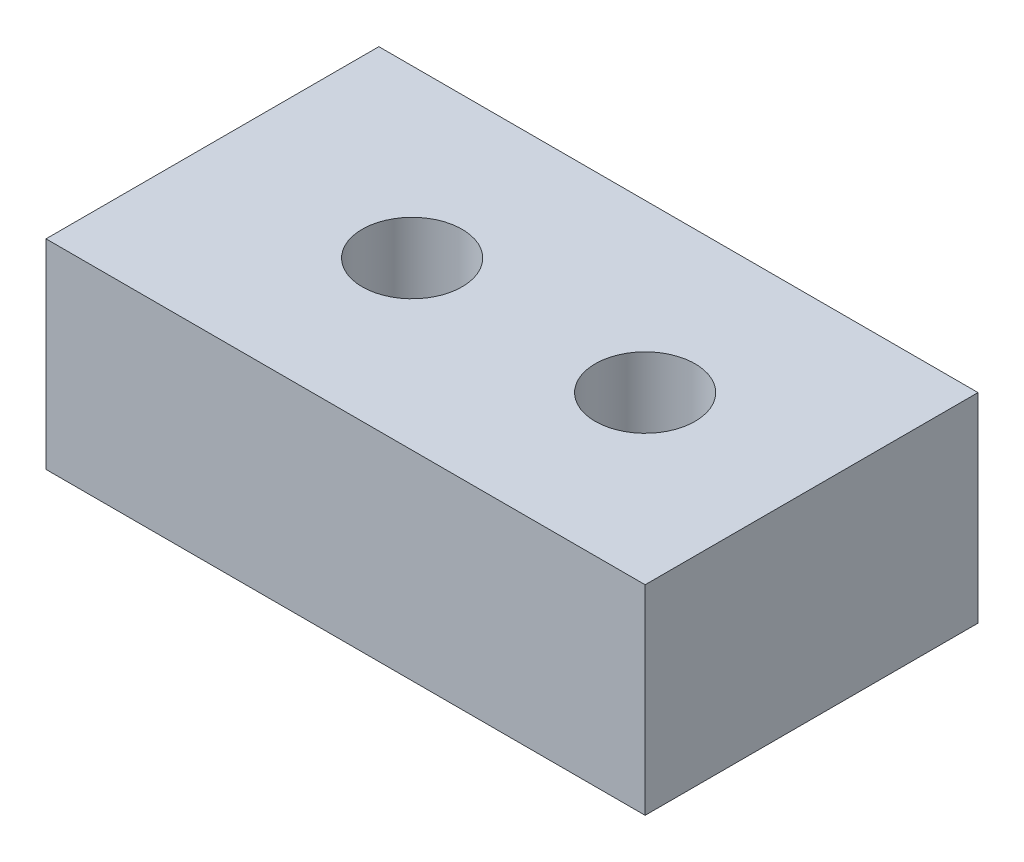
SolidWorks part; units mm, degrees
material "Balsa"
ref_plane "Front Plane" through (0, 0, 0) normal (0, 0, 1) x (1, 0, 0)
ref_plane "Top Plane" through (0, 0, 0) normal (0, 1, 0) x (1, 0, 0)
ref_plane "Right Plane" through (0, 0, 0) normal (1, 0, 0) x (0, 0, -1)
sketch "Sketch1" plane through (0, 0, 0) normal (0, 1, 0) x (1, 0, 0)
  line L1 (-9, -5) -> (9, -5)
  line L2 (-9, -5) -> (-9, 5)
  line L3 (-9, 5) -> (9, 5)
  line L4 (9, -5) -> (9, 5)
  line L5 (-9, -5) -> (9, 5) construction
  line L6 (-9, 5) -> (9, -5) construction
  point P0 (0, 0)
  dimension "D1" = 10
  dimension "D2" = 18
extrude "Boss-Extrude1" add sketch "Sketch1" along normal blind 6
sketch "Sketch2" plane through (0, 6, 0) normal (0, 1, 0) x (1, 0, 0)
  line L0 (-9, 0) -> (9, 0) construction
  line L1 (-9, 5) -> (-9, -5) construction
  line L2 (9, -5) -> (9, 5) construction
  circle A0 centre (-3, 0) radius 1.5
  circle A1 centre (4, 0) radius 1.5
  dimension "D1" = 3
  dimension "D2" = 3
  dimension "D3" = 7
  dimension "D4" = 6
  dimension "D5" = 5
extrude "Cut-Extrude1" cut sketch "Sketch2" against normal through all
